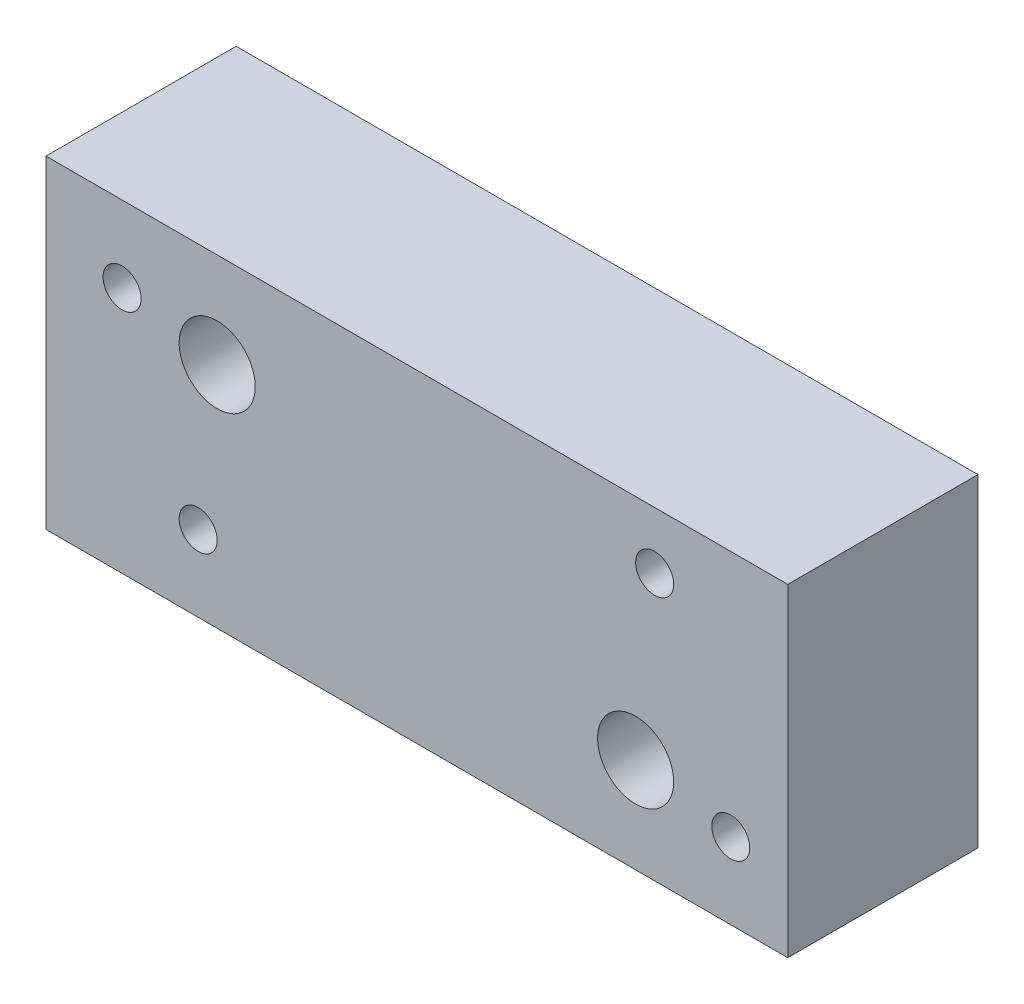
SolidWorks part; units mm, degrees
ref_plane "Front Plane" through (0, 0, 0) normal (0, 0, 1) x (1, 0, 0)
ref_plane "Top Plane" through (0, 0, 0) normal (0, 1, 0) x (1, 0, 0)
ref_plane "Right Plane" through (0, 0, 0) normal (1, 0, 0) x (0, 0, -1)
sketch "Sketch1" plane through (0, 0, 0) normal (0, 0, 1) x (1, 0, 0)
  line L1 (19.5, -8.5) -> (-19.5, -8.5)
  line L2 (19.5, -8.5) -> (19.5, 8.5)
  line L3 (19.5, 8.5) -> (-19.5, 8.5)
  line L4 (-19.5, -8.5) -> (-19.5, 8.5)
  line L5 (19.5, -8.5) -> (-19.5, 8.5) construction
  line L6 (19.5, 8.5) -> (-19.5, -8.5) construction
  circle A0 centre (-10.5, 3.5) radius 2
  circle A1 centre (-15.5, 4.5) radius 1
  circle A2 centre (-11.5, -4.5) radius 1
  circle A3 centre (11.5, -3.5) radius 2
  circle A4 centre (12.5, 5.5) radius 1
  circle A5 centre (16.5, -4.5) radius 1
  point P0 (0, 0)
  dimension "D3" = 4
  dimension "D4" = 2
  dimension "D5" = 4
  dimension "D6" = 4
  dimension "D7" = 8
  dimension "D8" = 4
  dimension "D9" = 5
  dimension "D10" = 8
  dimension "D11" = 7
  dimension "D12" = 4
  dimension "D13" = 4
  dimension "D14" = 3
  dimension "D15" = 9
  dimension "D16" = 23
  dimension "D1" = 39
  dimension "D2" = 17
extrude "Boss-Extrude1" add sketch "Sketch1" along normal mid plane 10
